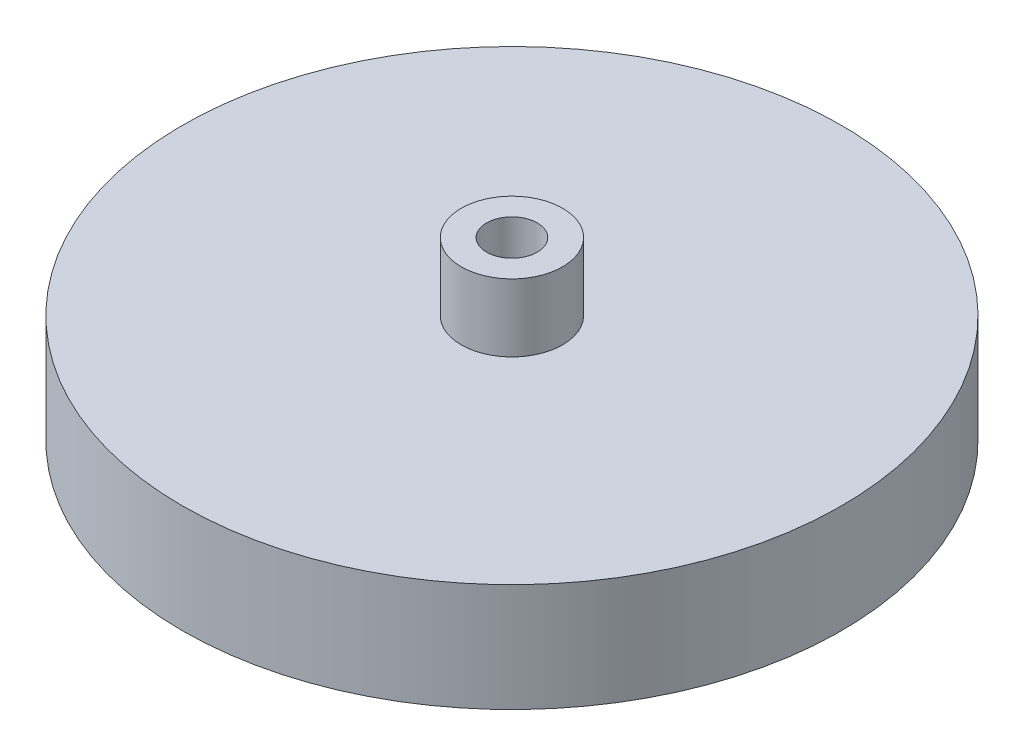
SolidWorks part; units mm, degrees
ref_plane "Front Plane" through (0, 0, 0) normal (0, 0, 1) x (1, 0, 0)
ref_plane "Top Plane" through (0, 0, 0) normal (0, 1, 0) x (1, 0, 0)
ref_plane "Right Plane" through (0, 0, 0) normal (1, 0, 0) x (0, 0, -1)
sketch "Sketch1" plane through (0, 0, 0) normal (0, 1, 0) x (1, 0, 0)
  circle A0 centre (0, 0) radius 61.9125
  dimension "D1" = 123.825
extrude "Boss-Extrude1" add sketch "Sketch1" along normal blind 20.32
sketch "Sketch2" plane through (0, 20.32, 0) normal (0, 1, 0) x (1, 0, 0)
  circle A0 centre (0, 0) radius 9.525
  dimension "D1" = 19.05
extrude "Boss-Extrude2" add sketch "Sketch2" along normal blind 12.7
sketch "Sketch3" plane through (0, 33.02, 0) normal (0, 1, 0) x (1, 0, 0)
  circle A0 centre (0, 0) radius 4.7625
  dimension "D1" = 9.525
extrude "Cut-Extrude1" cut sketch "Sketch3" against normal up to next
